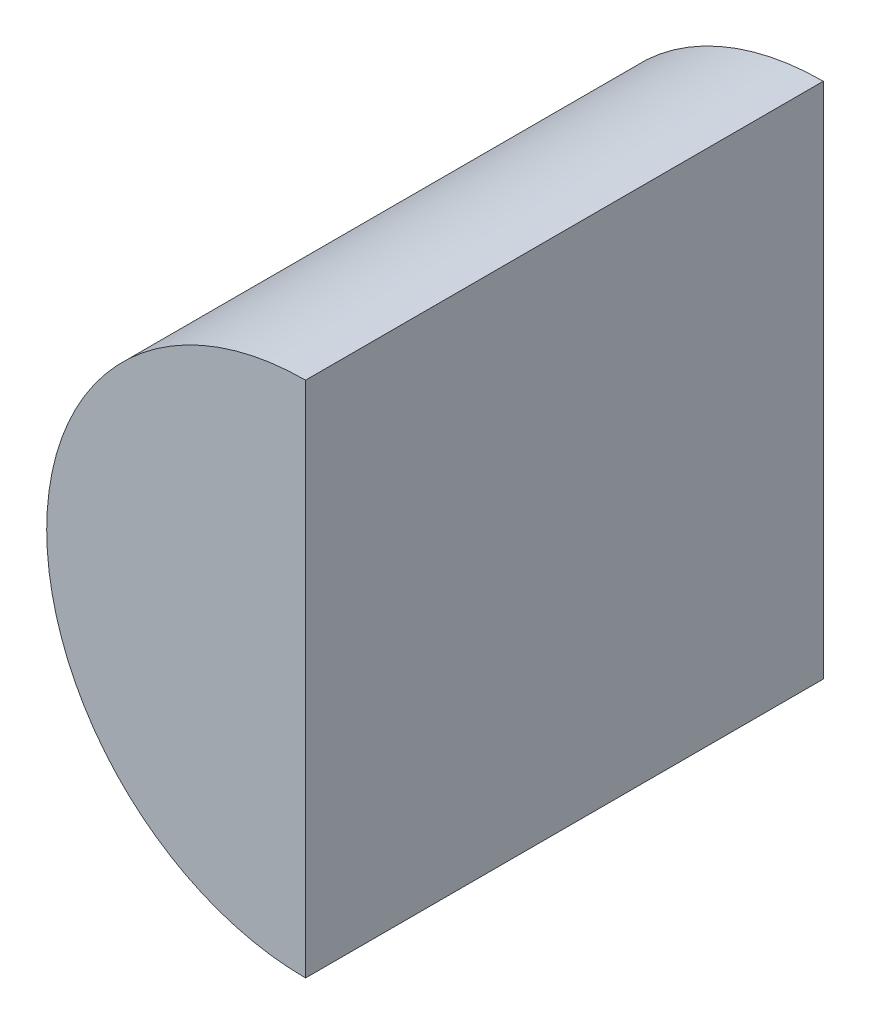
SolidWorks part; units mm, degrees
ref_plane "Alzado" through (0, 0, 0) normal (0, 0, 1) x (1, 0, 0)
ref_plane "Planta" through (0, 0, 0) normal (0, 1, 0) x (1, 0, 0)
ref_plane "Vista lateral" through (0, 0, 0) normal (1, 0, 0) x (0, 0, -1)
sketch "Croquis2" plane through (0, 0, 0) normal (0, 0, 1) x (1, 0, 0)
  line L0 (0, 25) -> (0, -25)
  arc A0 (0, 25) -> (0, -25) centre (0, 0) ccw
  dimension "D1" = 50
extrude "Saliente-Extruir1" add sketch "Croquis2" along normal blind 50
sketch "Croquis3" plane through (0, 0, 0) normal (0, 0, -1) x (-1, 0, 0)
  circle A0 centre (10.7466, 0) radius 5
  dimension "D1" = 10
extrude "Cortar-Extruir1" cut sketch "Croquis3" against normal blind 10
